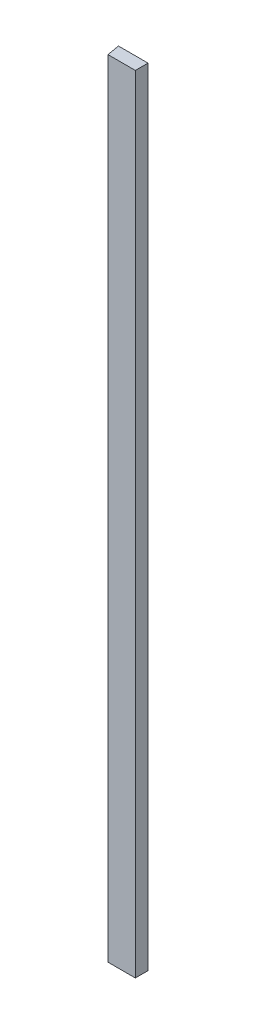
SolidWorks part; units mm, degrees
ref_plane "Front" through (0, 0, 0) normal (0, 0, 1) x (1, 0, 0)
ref_plane "Top" through (0, 0, 0) normal (0, 1, 0) x (1, 0, 0)
ref_plane "Right" through (0, 0, 0) normal (1, 0, 0) x (0, 0, -1)
sketch "Sketch1" plane through (0, 0, 0) normal (0, 1, 0) x (1, 0, 0)
  line L0 (-44.45, 19.05) -> (-37.7319, -19.05)
  line L1 (44.45, 19.05) -> (-44.45, 19.05)
  line L2 (44.45, 19.05) -> (44.45, -19.05)
  line L3 (44.45, -19.05) -> (-37.7319, -19.05)
  line L4 (-44.45, 19.05) -> (-44.45, -19.05) construction
  line L5 (44.45, 19.05) -> (-44.45, -19.05) construction
  line L6 (44.45, -19.05) -> (-44.45, 19.05) construction
  line L7 (-37.7319, -19.05) -> (-44.45, -19.05) construction
  point P0 (0, 0)
  dimension "D1" = 38.1
  dimension "D2" = 88.9
  dimension "D3" = 80
extrude "Boss-Extrude1" add sketch "Sketch1" along normal blind 2362.2
fillet "Fillet2" [suppressed] radius 3.175
